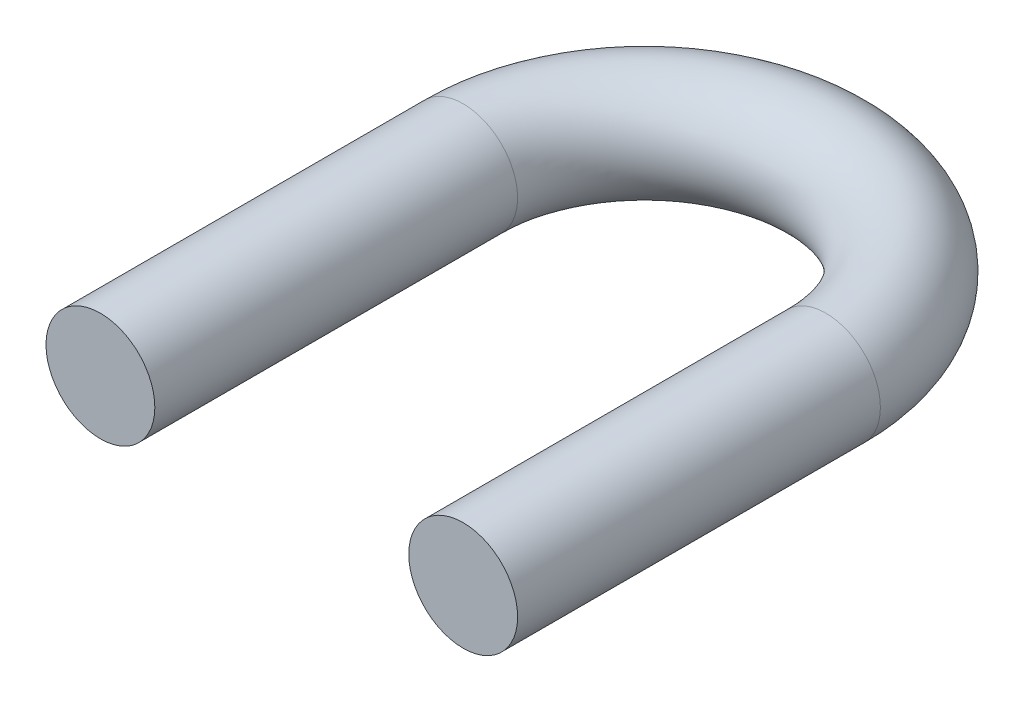
SolidWorks part; units mm, degrees
ref_plane "Front Plane" through (0, 0, 0) normal (0, 0, 1) x (1, 0, 0)
ref_plane "Top Plane" through (0, 0, 0) normal (0, 1, 0) x (1, 0, 0)
ref_plane "Right Plane" through (0, 0, 0) normal (1, 0, 0) x (0, 0, -1)
sketch "Sketch1" plane through (0, 0, 0) normal (0, 1, 0) x (1, 0, 0)
  line L0 (-10, 0) -> (-10, -20)
  line L1 (10, 0) -> (10, -20)
  arc A0 (10, 0) -> (-10, 0) centre (0, 0) ccw
  point P7 (10, -21.0762)
  point P8 (-10, -24.6637)
  dimension "D1" = 20
  dimension "D2" = 20
sweep "Sweep1" add path "Sketch1" circular profile diameter 6 parameters "D3"=6
